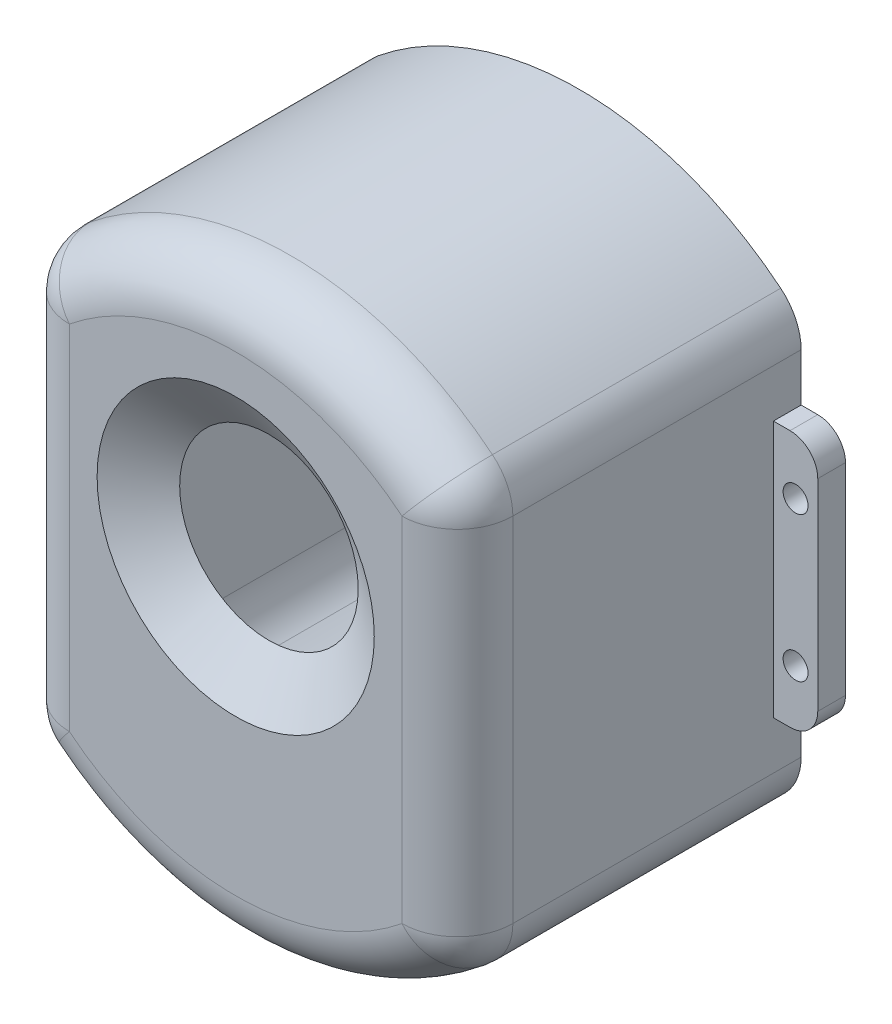
SolidWorks part; units mm, degrees
ref_plane "Front Plane" through (0, 0, 0) normal (0, 0, 1) x (1, 0, 0)
ref_plane "Top Plane" through (0, 0, 0) normal (0, 1, 0) x (1, 0, 0)
ref_plane "Right Plane" through (0, 0, 0) normal (1, 0, 0) x (0, 0, -1)
sketch "Sketch2" plane through (0, 0, 0) normal (0, 0, 1) x (1, 0, 0)
  line L0 (55, 0) -> (-55, 0) construction
  line L5 (-40, 36.3068) -> (-40, -36.3068)
  line L7 (40, 36.3068) -> (40, -36.3068)
  line L9 (0, -55) -> (0, 55) construction
  arc A2 (-40, 36.3068) -> (40, 36.3068) centre (0, -5) cw
  arc A3 (-40, -36.3068) -> (40, -36.3068) centre (0, 5) ccw
  point P4 (52.4868, 35.6983)
  point P5 (-40, 0)
  point P10 (0, 52.5)
  point P11 (0, -52.5)
  point P12 (-63.7654, -26.237)
  point P15 (0, 0)
  point P16 (-41.1455, 14.6536)
  dimension "D2" = 57.5
  dimension "D1" = 80
  dimension "D3" = 105
extrude "Boss-Extrude1" add sketch "Sketch2" along normal blind 62
shell "Shell1" thickness 6
fillet "Fillet2" radius 10 8 edges at (40, 0, 62) (0, -52.5, 62) (-40, 0, 62) (0, 52.5, 62) (40, -36.3068, 31) (40, 36.3068, 31) (-40, 36.3068, 31) (-40, -36.3068, 31)
fillet "Fillet3" radius 10 4 edges at (34, 33.6814, 28) (34, -33.6814, 28) (-34, 33.6814, 28) (-34, -33.6814, 28)
sketch "Sketch4" plane through (0, 0, 0) normal (0, 0, 1) x (1, 0, 0)
  line L0 (0, -34.1) -> (0, 34.1) construction
  line L1 (-21.1, -28.0819) -> (21.1, -28.0819)
  line L2 (-21.1, -28.0819) -> (-21.1, -56.0464)
  line L3 (-21.1, -56.0464) -> (21.1, -56.0464)
  line L4 (21.1, -28.0819) -> (21.1, -56.0464)
  point P4 (0, -28.0819)
  dimension "D1" = 42.2
extrude "Cut-Extrude1" cut sketch "Sketch4" along normal blind 1.9
sketch "Sketch5" plane through (0, 0, 62) normal (0, 0, 1) x (1, 0, 0)
  line L0 (0, -34.1) -> (0, 34.1) construction
  circle A0 centre (0, 10.5) radius 25
  arc A1 (30, 31.8273) -> (-30, 31.8273) centre (0, -5) ccw construction
  point P4 (0, 14.4692)
  point P8 (0, 42.5)
  dimension "D1" = 50
  dimension "D2" = 32
extrude "Cut-Extrude2" cut sketch "Sketch5" against normal through all
draft "Draft1" type of draft neutral plane draft angle 56 faces to draft 1 face at (-25, 10.5, 56) neutral plane through (0, -5, 62) neutral plane normal (0, 0, 1) parameters "D1"=56
sketch "Sketch6" plane through (0, 0, 0) normal (0, 0, 1) x (1, 0, 0)
  line L0 (40, 31.8273) -> (40, -31.8273) construction
  line L1 (40, 23.1767) -> (48, 23.1767)
  line L2 (40, 23.1767) -> (40, -23.1767)
  line L3 (40, -23.1767) -> (48, -23.1767)
  line L4 (48, 23.1767) -> (48, -23.1767)
  line L5 (34.1, 0) -> (-34.1, 0) construction
  line L6 (44, 13.0559) -> (44, -13.0559) construction
  line L7 (0, -34.1) -> (0, 34.1) construction
  line L8 (-44, 13.0559) -> (-44, -13.0559) construction
  line L9 (-48, 23.1767) -> (-48, -23.1767)
  line L10 (-40, -23.1767) -> (-48, -23.1767)
  line L11 (-40, 23.1767) -> (-40, -23.1767)
  line L12 (-40, 23.1767) -> (-48, 23.1767)
  circle A0 centre (44, 13.0559) radius 2.25
  circle A1 centre (44, -13.0559) radius 2.25
  circle A2 centre (-44, -13.0559) radius 2.25
  circle A3 centre (-44, 13.0559) radius 2.25
  point P6 (48, 0)
  point P11 (44, 0)
  point P12 (44, 23.1767)
  dimension "D1" = 4.5
  dimension "D2" = 8
extrude "Boss-Extrude2" add sketch "Sketch6" along normal blind 5
fillet "Fillet4" radius 5 4 edges at (48, -23.1767, 2.5) (48, 23.1767, 2.5) (-48, -23.1767, 2.5) (-48, 23.1767, 2.5)
